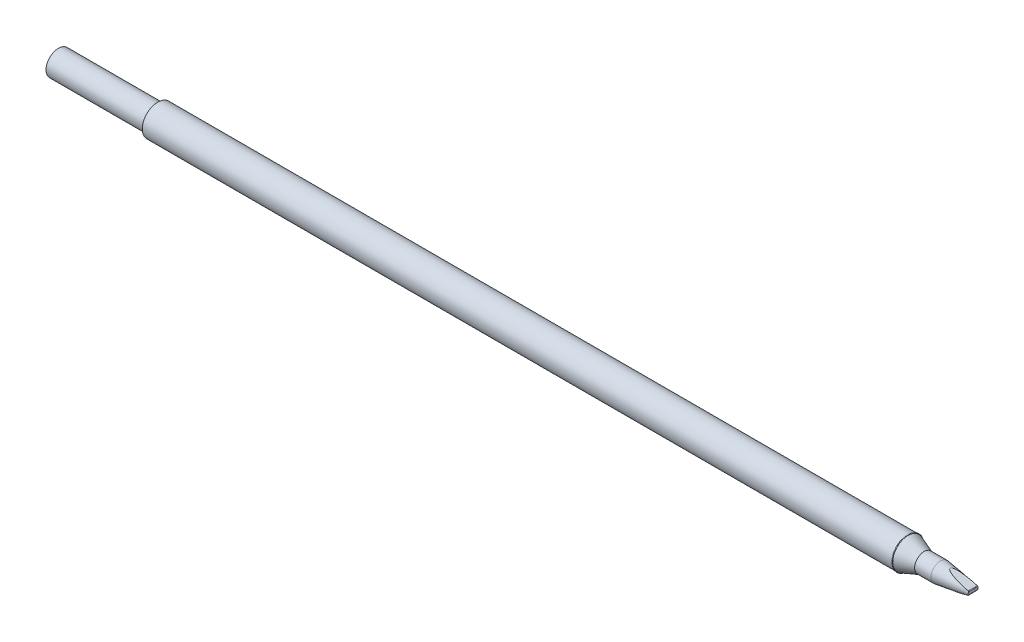
SolidWorks part; units mm, degrees
ref_plane "Front Plane" through (0, 0, 0) normal (0, 0, 1) x (1, 0, 0)
ref_plane "Top Plane" through (0, 0, 0) normal (0, 1, 0) x (1, 0, 0)
ref_plane "Right Plane" through (0, 0, 0) normal (1, 0, 0) x (0, 0, -1)
sketch "Sketch1" plane through (0, 0, 0) normal (0, 0, 1) x (1, 0, 0)
  line L0 (0, 0) -> (115, 0) construction
  line L1 (0, 0) -> (-15, 0)
  line L2 (-15, 0) -> (-15, 0.5)
  line L3 (-15, 0.5) -> (0, 0.5)
  line L4 (0, 0.5) -> (0, 1.49)
  line L5 (0, 1.49) -> (-15, 1.49)
  line L6 (-15, 1.49) -> (-15, 1.9)
  line L7 (-15, 1.9) -> (0, 1.9)
  line L8 (0, 1.9) -> (0, 2.365)
  line L9 (0, 2.365) -> (115, 2.365)
  line L10 (115, 2.365) -> (117.5, 1.45)
  line L11 (117.5, 1.45) -> (120, 1.45)
  line L12 (120, 1.45) -> (125, 0.75)
  line L13 (125, 0.75) -> (125, 0)
  line L14 (125, 0) -> (0, 0)
  point P3 (114.2137, -0.38)
  point P17 (114.0235, 0.5)
  point P18 (115, 0)
  dimension "D1" = 1.9
  dimension "D2" = 2.365
  dimension "D3" = 0.41
  dimension "D4" = 0.5
  dimension "D5" = 15
  dimension "D6" = 2.5
  dimension "D7" = 1.45
  dimension "D8" = 2.5
  dimension "D9" = 5
  dimension "D10" = 0.75
  dimension "D11" = 115
revolve "Revolve1" add sketch "Sketch1" angle 360 about L0
fillet "Fillet1" radius 0.45 1 edges at (-15, 0, 0.5)
chamfer "Chamfer1" distance 0.2 angle 60 1 edges at (0, 0, 2.365)
sketch "Sketch2" plane through (0, 0, 0) normal (0, 0, 1) x (1, 0, 0)
  line L0 (0, 0) -> (128.6887, 0) construction
  circle A0 centre (115, 2.365) radius 0.05
  point P3 (115, 2.415)
  dimension "D1" = 2.415
revolve "Revolve2" add sketch "Sketch2" angle 360 about L0
sketch "Sketch3" plane through (0, 0, 0) normal (0, 0, 1) x (1, 0, 0)
  line L0 (120, 1.65) -> (126, 0)
  line L1 (120, 1.65) -> (129.1593, 1.65)
  line L2 (129.1593, 1.65) -> (129.1593, -1.65)
  line L3 (129.1593, -1.65) -> (120, -1.65)
  line L4 (120, -1.65) -> (126, 0)
  line L5 (126, 0) -> (129.1593, 0) construction
  line L6 (126, 0) -> (0, 0) construction
  line L7 (120, 1.45) -> (120, -1.45) construction
  point P4 (120, 0)
  point P11 (0, 0)
  point P12 (0, 0)
  point P13 (0, 0)
  dimension "D1" = 6
  dimension "D2" = 0
  dimension "D3" = 0.2
extrude "Cut-Extrude1" cut sketch "Sketch3" against normal mid plane 10
fillet "Fillet3" radius 0.1 2 edges at (125, -0.275, 0) (125, 0.275, 0)
